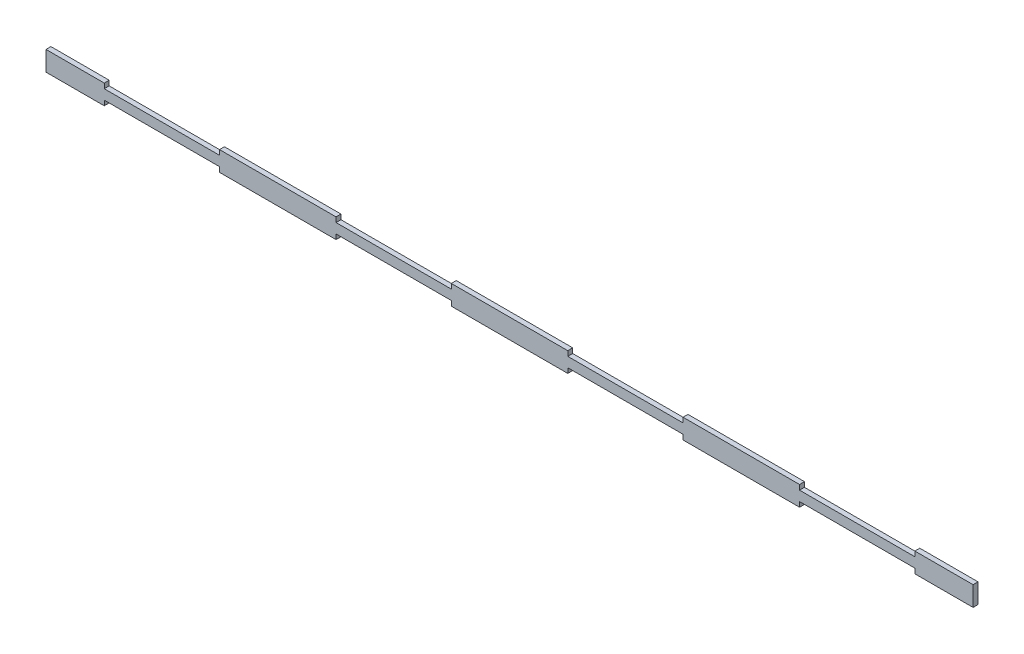
SolidWorks part; units mm, degrees
material "Acrylique (impact moyen-haut)"
ref_plane "Plan de face" through (0, 0, 0) normal (0, 0, 1) x (1, 0, 0)
ref_plane "Plan de dessus" through (0, 0, 0) normal (0, 1, 0) x (1, 0, 0)
ref_plane "Plan de droite" through (0, 0, 0) normal (1, 0, 0) x (0, 0, -1)
sketch "Esquisse1" plane through (0, 0, 0) normal (0, 0, 1) x (1, 0, 0)
  line L0 (261.0438, -3.175) -> (186.6313, -3.175) construction
  line L1 (298.45, 0) -> (-298.45, 0)
  line L2 (298.45, 0) -> (298.45, -12.7)
  line L3 (298.45, -12.7) -> (-298.45, -12.7)
  line L4 (-298.45, 0) -> (-298.45, -12.7)
  line L5 (261.0438, -3.175) -> (186.6313, -3.175) construction
  line L6 (-186.6313, -3.175) -> (-261.0438, -3.175) construction
  line L7 (-37.4063, -3.175) -> (-111.8188, -3.175) construction
  line L8 (111.8188, -3.175) -> (37.4062, -3.175) construction
  line L9 (-186.6313, -3.175) -> (-261.0438, -3.175) construction
  line L10 (-37.4063, -3.175) -> (-111.8188, -3.175) construction
  line L11 (111.8188, -3.175) -> (37.4062, -3.175) construction
  line L12 (261.0438, 0) -> (261.0438, -3.175) construction
  line L13 (186.7313, -3.175) -> (260.9438, -3.175)
  line L14 (186.7313, -3.175) -> (186.7313, 0)
  line L15 (186.7313, 0) -> (260.9438, 0)
  line L16 (260.9438, -3.175) -> (260.9438, 0)
  line L17 (186.7313, -3.175) -> (260.9438, 0) construction
  line L18 (186.7313, 0) -> (260.9438, -3.175) construction
  line L19 (186.6313, 0) -> (186.6313, -3.175) construction
  line L20 (37.4062, 0) -> (37.4062, -3.175) construction
  line L21 (37.5062, -3.175) -> (111.7188, -3.175)
  line L22 (37.5062, -3.175) -> (37.5062, 0)
  line L23 (37.5062, 0) -> (111.7188, 0)
  line L24 (111.7188, -3.175) -> (111.7188, 0)
  line L25 (37.5062, -3.175) -> (111.7188, 0) construction
  line L26 (37.5062, 0) -> (111.7188, -3.175) construction
  line L27 (111.8188, 0) -> (111.8188, -3.175) construction
  line L28 (-111.8188, 0) -> (-111.8188, -3.175) construction
  line L29 (-111.7188, -3.175) -> (-37.5063, -3.175)
  line L30 (-111.7188, -3.175) -> (-111.7188, 0)
  line L31 (-111.7188, 0) -> (-37.5063, 0)
  line L32 (-37.5063, -3.175) -> (-37.5063, 0)
  line L33 (-111.7188, -3.175) -> (-37.5063, 0) construction
  line L34 (-111.7188, 0) -> (-37.5063, -3.175) construction
  line L35 (-37.4063, 0) -> (-37.4063, -3.175) construction
  line L36 (-186.6313, 0) -> (-186.6313, -3.175) construction
  line L37 (-260.9438, -3.175) -> (-186.7313, -3.175)
  line L38 (-260.9438, -3.175) -> (-260.9438, 0)
  line L39 (-260.9438, 0) -> (-186.7313, 0)
  line L40 (-186.7313, -3.175) -> (-186.7313, 0)
  line L41 (-260.9438, -3.175) -> (-186.7313, 0) construction
  line L42 (-260.9438, 0) -> (-186.7313, -3.175) construction
  line L43 (-261.0438, 0) -> (-261.0438, -3.175) construction
  line L44 (298.45, -6.35) -> (-298.45, -6.35) construction
  line L45 (-260.9438, -12.7) -> (-186.7313, -9.525) construction
  line L46 (-260.9438, -9.525) -> (-186.7313, -12.7) construction
  line L47 (-111.7188, -12.7) -> (-37.5063, -9.525) construction
  line L48 (-111.7188, -9.525) -> (-37.5063, -12.7) construction
  line L49 (37.5062, -12.7) -> (111.7188, -9.525) construction
  line L50 (37.5062, -9.525) -> (111.7188, -12.7) construction
  line L51 (186.7313, -12.7) -> (260.9438, -9.525) construction
  line L52 (186.7313, -9.525) -> (260.9438, -12.7) construction
  line L53 (111.8188, -9.525) -> (37.4062, -9.525) construction
  line L54 (-37.4063, -9.525) -> (-111.8188, -9.525) construction
  line L55 (-186.6313, -9.525) -> (-261.0438, -9.525) construction
  line L56 (261.0438, -9.525) -> (186.6313, -9.525) construction
  line L57 (-186.7313, -9.525) -> (-186.7313, -12.7)
  line L58 (-260.9438, -12.7) -> (-186.7313, -12.7)
  line L59 (-260.9438, -9.525) -> (-260.9438, -12.7)
  line L60 (-260.9438, -9.525) -> (-186.7313, -9.525)
  line L61 (-37.5063, -9.525) -> (-37.5063, -12.7)
  line L62 (-111.7188, -12.7) -> (-37.5063, -12.7)
  line L63 (-111.7188, -9.525) -> (-111.7188, -12.7)
  line L64 (-111.7188, -9.525) -> (-37.5063, -9.525)
  line L65 (111.7188, -9.525) -> (111.7188, -12.7)
  line L66 (37.5062, -12.7) -> (111.7188, -12.7)
  line L67 (37.5062, -9.525) -> (37.5062, -12.7)
  line L68 (37.5062, -9.525) -> (111.7188, -9.525)
  line L69 (260.9438, -9.525) -> (260.9438, -12.7)
  line L70 (186.7313, -12.7) -> (260.9438, -12.7)
  line L71 (186.7313, -9.525) -> (186.7313, -12.7)
  line L72 (186.7313, -9.525) -> (260.9438, -9.525)
  point P14 (223.8375, -1.5875)
  point P23 (74.6125, -1.5875)
  point P32 (-74.6125, -1.5875)
  point P41 (-223.8375, -1.5875)
  point P76 (-223.8375, -11.1125)
  point P77 (-74.6125, -11.1125)
  point P78 (74.6125, -11.1125)
  point P79 (223.8375, -11.1125)
  dimension "D1" = 3.175
  dimension "D2" = 0.1
  dimension "D3" = 0.1
  dimension "D4" = 3.175
  dimension "D5" = 0.1
  dimension "D6" = 0.1
  dimension "D7" = 3.175
  dimension "D8" = 0.1
  dimension "D9" = 0.1
  dimension "D10" = 3.175
  dimension "D11" = 0.1
  dimension "D12" = 0.1
extrude "Boss.-Extru.1" add sketch "Esquisse1" against normal blind 3.175 contours L71 L72 L69 L3 L2 L1 L16 L13 L14 L24 L21 L22 L32 L29 L30 L40 L37 L38 L4 L59 L60 L57 L63 L64 L61 L67 L68 L65
